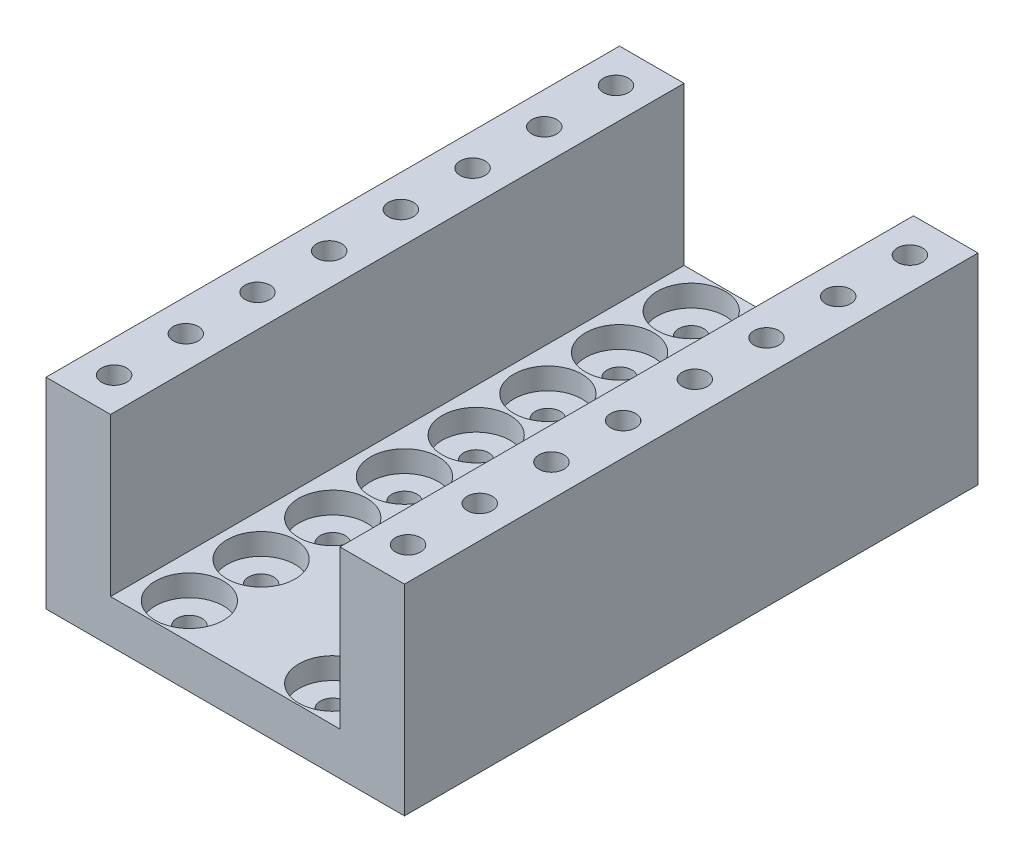
SolidWorks part; units mm, degrees
ref_plane "Front Plane" through (0, 0, 0) normal (0, 0, 1) x (1, 0, 0)
ref_plane "Top Plane" through (0, 0, 0) normal (0, 1, 0) x (1, 0, 0)
ref_plane "Right Plane" through (0, 0, 0) normal (1, 0, 0) x (0, 0, -1)
sketch "Sketch1" plane through (0, 0, 0) normal (0, 0, 1) x (1, 0, 0)
  line L0 (16, 14) -> (25, 14)
  line L1 (-25, 14) -> (-16, 14)
  line L2 (-25, 14) -> (-25, -14)
  line L3 (-25, -14) -> (25, -14)
  line L4 (25, 14) -> (25, -14)
  line L5 (-25, 14) -> (25, -14) construction
  line L6 (-25, -14) -> (25, 14) construction
  line L8 (-16, 14) -> (-16, -8)
  line L9 (-16, -8) -> (16, -8)
  line L10 (16, 14) -> (16, -8)
  point P0 (0, 0)
  point P6 (0, 14.1034)
  dimension "D1" = 32
  dimension "D2" = 22
  dimension "D3" = 28
  dimension "D4" = 50
extrude "Boss-Extrude1" add sketch "Sketch1" along normal blind 80
sketch "Sketch2" plane through (0, -8, 0) normal (0, 1, 0) x (1, 0, 0)
  line L0 (0, 0) -> (0, -5) construction
  line L1 (-10, -5) -> (10, -5) construction
  line L2 (16, 0) -> (-16, 0) construction
  circle A0 centre (-10, -5) radius 1.75
  circle A1 centre (10, -5) radius 1.75
  dimension "D1" = 3.5
  dimension "D2" = 5
  dimension "D3" = 20
extrude "Cut-Extrude1" cut sketch "Sketch2" against normal through all
sketch "Sketch3" plane through (0, -8, 0) normal (0, 1, 0) x (1, 0, 0)
  circle A6 centre (-10, -5) radius 4.75
  circle A7 centre (-10, -5) radius 4.75
  circle A9 centre (10, -5) radius 4.75
  circle A10 centre (10, -5) radius 4.75
  dimension "D1" = 3
  dimension "D2" = 3
extrude "Cut-Extrude2" cut sketch "Sketch3" against normal blind 3
sketch "Sketch4" plane through (0, 14, 0) normal (0, 1, 0) x (1, 0, 0)
  line L0 (-20.5, -5) -> (20.5, -5) construction
  line L1 (0, -5) -> (0, 0) construction
  line L2 (16, 0) -> (-16, 0) construction
  line L3 (-25, -80) -> (-25, 0) construction
  circle A0 centre (-20.5, -5) radius 1.75
  circle A1 centre (20.5, -5) radius 1.75
  circle A2 centre (10, -5) radius 1.75 construction
  dimension "D1" = 5
  dimension "D2" = 4.5
extrude "Cut-Extrude3" cut sketch "Sketch4" against normal through all
pattern_linear "LPattern1" count 8 spacing 10 along (0, 0, 1) of "Cut-Extrude1", "Cut-Extrude2", "Cut-Extrude3"
